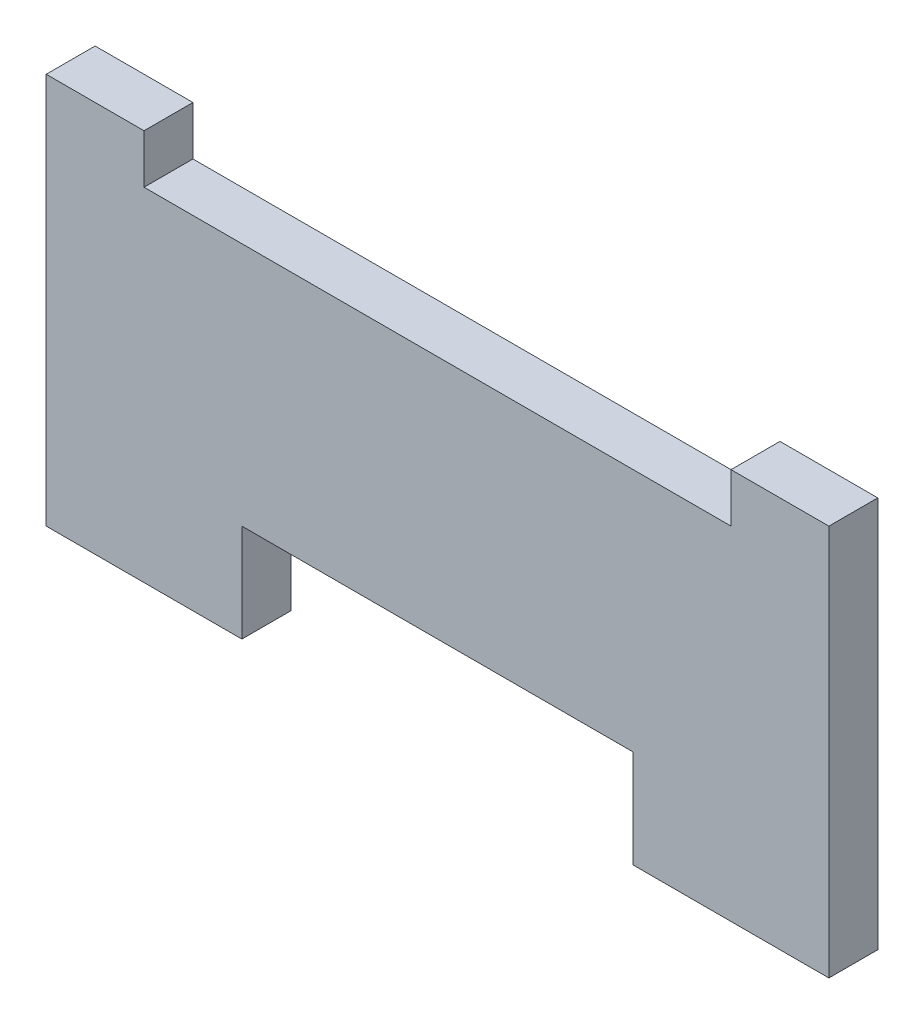
SolidWorks part; units mm, degrees
ref_plane "Alzado" through (0, 0, 0) normal (0, 0, 1) x (1, 0, 0)
ref_plane "Planta" through (0, 0, 0) normal (0, 1, 0) x (1, 0, 0)
ref_plane "Vista lateral" through (0, 0, 0) normal (1, 0, 0) x (0, 0, -1)
sketch "Croquis1" plane through (0, 0, 0) normal (0, 0, 1) x (1, 0, 0)
  line L1 (0, 0) -> (8, 0)
  line L2 (0, 0) -> (0, 4)
  line L3 (0, 4) -> (8, 4)
  line L4 (8, 0) -> (8, 4)
  dimension "D1" = 8
  dimension "D2" = 4
extrude "Saliente-Extruir1" add sketch "Croquis1" along normal blind 0.5
sketch "Croquis2" plane through (0, 0, 0.5) normal (0, 0, 1) x (1, 0, 0)
  line L0 (8, 4) -> (0, 4) construction
  line L1 (1, 4) -> (7, 4)
  line L2 (1, 4) -> (1, 3.5)
  line L3 (1, 3.5) -> (7, 3.5)
  line L4 (7, 4) -> (7, 3.5)
  line L5 (4, 3.5) -> (4, 0) construction
  line L6 (0, 0) -> (8, 0) construction
  line L8 (2, 0) -> (6, 0)
  line L9 (2, 0) -> (2, 1)
  line L10 (2, 1) -> (6, 1)
  line L11 (6, 0) -> (6, 1)
  point P14 (4, 1)
  dimension "D1" = 0.5
  dimension "D2" = 6
  dimension "D3" = 4
  dimension "D4" = 1
extrude "Cortar-Extruir1" cut sketch "Croquis2" against normal blind 0.5
